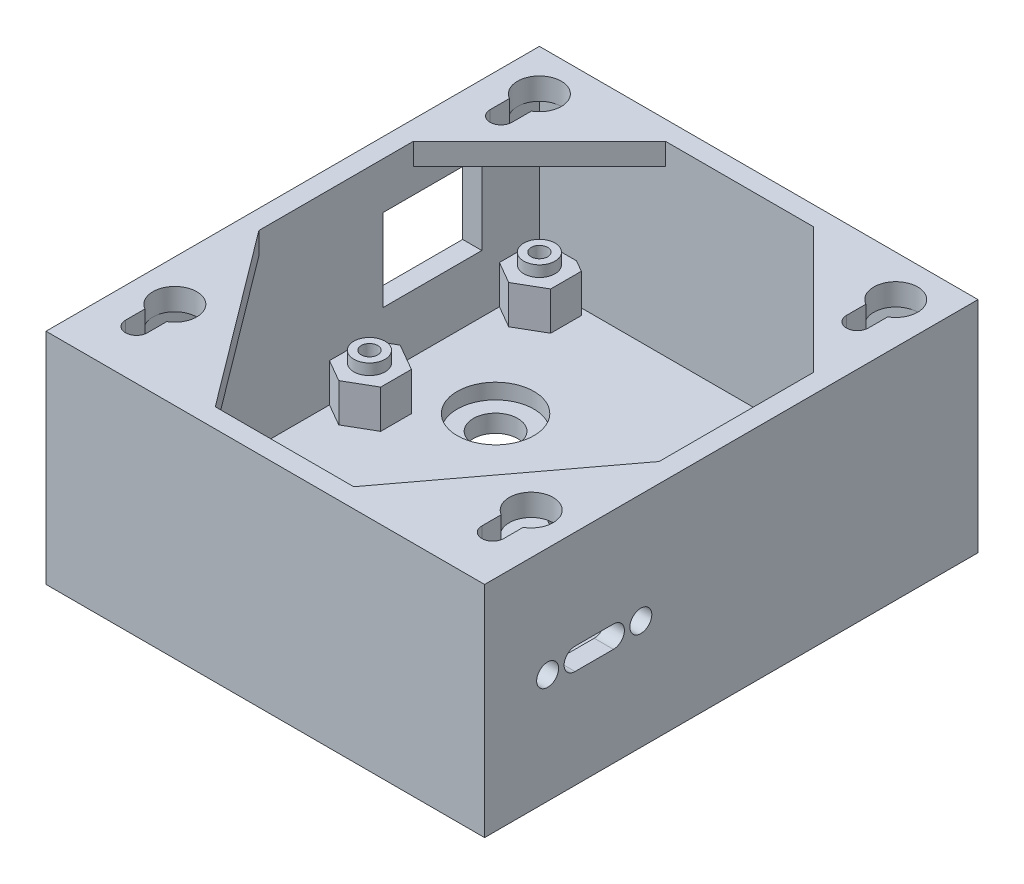
SolidWorks part; units mm, degrees
ref_plane "Front Plane" through (0, 0, 0) normal (0, 0, 1) x (1, 0, 0)
ref_plane "Top Plane" through (0, 0, 0) normal (0, 1, 0) x (1, 0, 0)
ref_plane "Right Plane" through (0, 0, 0) normal (1, 0, 0) x (0, 0, -1)
sketch "Sketch1" plane through (0, 0, 0) normal (0, 1, 0) x (1, 0, 0)
  line L1 (-40, -45) -> (40, -45)
  line L2 (-40, -45) -> (-40, 45)
  line L3 (-40, 45) -> (40, 45)
  line L4 (40, -45) -> (40, 45)
  line L5 (-40, -45) -> (40, 45) construction
  line L6 (-40, 45) -> (40, -45) construction
  point P0 (0, 0)
  dimension "D1" = 80
  dimension "D2" = 90
extrude "Boss-Extrude1" add sketch "Sketch1" along normal blind 6
sketch "Sketch4" plane through (0, 6, 0) normal (0, 1, 0) x (1, 0, 0)
  line L0 (40, -45) -> (40, 45) construction
  line L1 (-40, 45) -> (40, 45)
  line L2 (-40, 45) -> (-40, -45)
  line L3 (-40, -45) -> (40, -45)
  line L4 (40, 45) -> (40, -45)
  line L5 (-36.5, 41.5) -> (36.5, 41.5)
  line L6 (-36.5, 41.5) -> (-36.5, -41.5)
  line L7 (-36.5, -41.5) -> (36.5, -41.5)
  line L8 (36.5, 41.5) -> (36.5, -41.5)
  dimension "D1" = 3.5
  dimension "D2" = 3.5
  dimension "D3" = 3.5
  dimension "D4" = 3.5
extrude "Boss-Extrude2" add sketch "Sketch4" along normal blind 34 contours L2 L1 L4 L3 | L6 L5 L8 L7
sketch "Sketch5" plane through (0, 6, 0) normal (0, 1, 0) x (1, 0, 0)
  line L0 (-40, 45) -> (40, 45) construction
  line L1 (-36.5, 41.5) -> (-36.5, -41.5) construction
  line L2 (-36.5, 41.5) -> (-36.5, -41.5) construction
  circle A0 centre (-32.5, 37.5) radius 1.5
  circle A1 centre (-32.5, 6.5) radius 1.5
  dimension "D1" = 3
  dimension "D4" = 3
  dimension "D2" = 7.5
  dimension "D3" = 4
  dimension "D5" = 31
  dimension "D6" = 4
sketch "Sketch6" plane through (0, 6, 0) normal (0, 1, 0) x (1, 0, 0)
  line L0 (-40, 45) -> (-40, -45) construction
  line L1 (-40, 45) -> (40, 45) construction
  line L2 (-40, -45) -> (40, -45) construction
  circle A0 centre (-20, 17) radius 4.05
  circle A1 centre (-20, -25) radius 4.05
  dimension "D2" = 8.1
  dimension "D3" = 8.1
  dimension "D4" = 28
  dimension "D5" = 20
  dimension "D1" = 20
extrude "Cut-Extrude1" cut sketch "Sketch6" against normal blind 40
sketch "Sketch7" plane through (0, 6, 0) normal (0, 1, 0) x (1, 0, 0)
  circle A0 centre (-20, 17) radius 7
  circle A1 centre (-20, -25) radius 7
  dimension "D1" = 14
  dimension "D2" = 14
extrude "Cut-Extrude2" cut sketch "Sketch7" against normal blind 2.8
sketch "Sketch8" plane through (0, 6, 0) normal (0, 1, 0) x (1, 0, 0)
  line L0 (-36.5, 41.5) -> (-36.5, -41.5) construction
  line L1 (-29.65, 39.1454) -> (-32.5, 40.7909)
  line L2 (-32.5, 40.7909) -> (-35.35, 39.1454)
  line L3 (-35.35, 39.1454) -> (-35.35, 35.8546)
  line L4 (-35.35, 35.8546) -> (-32.5, 34.2091)
  line L5 (-32.5, 34.2091) -> (-29.65, 35.8546)
  line L6 (-29.65, 35.8546) -> (-29.65, 39.1454)
  line L8 (-29.65, 8.1454) -> (-32.5, 9.7909)
  line L9 (-32.5, 9.7909) -> (-35.35, 8.1454)
  line L10 (-35.35, 8.1454) -> (-35.35, 4.8546)
  line L11 (-35.35, 4.8546) -> (-32.5, 3.2091)
  line L12 (-32.5, 3.2091) -> (-29.65, 4.8546)
  line L13 (-29.65, 4.8546) -> (-29.65, 8.1454)
  circle A0 centre (-32.5, 37.5) radius 2.85 construction
  circle A1 centre (-32.5, 6.5) radius 2.85 construction
  point P40 (-33.925, 8.9682)
  dimension "D1" = 5.7
  dimension "D4" = 5.7
sketch "Sketch10" plane through (0, 6, 0) normal (0, 1, 0) x (1, 0, 0)
  line L1 (-32.5, 43.1003) -> (-37.35, 40.3001)
  line L2 (-37.35, 40.3001) -> (-37.35, 34.6999)
  line L3 (-37.35, 34.6999) -> (-32.5, 31.8997)
  line L4 (-32.5, 31.8997) -> (-27.65, 34.6999)
  line L5 (-27.65, 34.6999) -> (-27.65, 40.3001)
  line L6 (-27.65, 40.3001) -> (-32.5, 43.1003)
  line L19 (-27.65, 9.3001) -> (-32.5, 12.1003)
  line L20 (-32.5, 12.1003) -> (-37.35, 9.3001)
  line L21 (-37.35, 9.3001) -> (-37.35, 3.6999)
  line L22 (-37.35, 3.6999) -> (-32.5, 0.8997)
  line L23 (-32.5, 0.8997) -> (-27.65, 3.6999)
  line L24 (-27.65, 3.6999) -> (-27.65, 9.3001)
  line L25 (-36.5, 41.5) -> (-36.5, -41.5) construction
  line L27 (-32.5, 34.2091) -> (-29.65, 35.8546) construction
  line L28 (-32.5, 3.2091) -> (-29.65, 4.8546) construction
  circle A0 centre (-32.5, 37.5) radius 4.85 construction
  circle A3 centre (-32.5, 6.5) radius 4.85 construction
  dimension "D1" = 2
  dimension "D2" = 2
extrude "Boss-Extrude3" add sketch "Sketch10" along normal blind 7
sketch "Sketch11" plane through (0, 13, 0) normal (0, 1, 0) x (1, 0, 0)
  circle A0 centre (-32.5, 37.5) radius 2.85
  circle A3 centre (-32.5, 6.5) radius 2.85
  dimension "D1" = 5.7
  dimension "D2" = 5.7
extrude "Boss-Extrude4" add sketch "Sketch11" along normal blind 2
extrude "Cut-Extrude3" cut sketch "Sketch5" against normal blind 6 and the other way blind 9
extrude "Cut-Extrude4" cut sketch "Sketch8" against normal through all and the other way blind 6
sketch "Sketch12" plane through (-36.5, 0, 0) normal (1, 0, 0) x (0, 0, -1)
  line L0 (45, 0) -> (-45, 0) construction
  line L1 (31, 16.5) -> (13, 16.5)
  line L2 (31, 16.5) -> (31, 31.5)
  line L3 (31, 31.5) -> (13, 31.5)
  line L4 (13, 16.5) -> (13, 31.5)
  line L5 (45, 40) -> (45, 0) construction
  dimension "D1" = 18
  dimension "D2" = 15
  dimension "16.5mm" = 16.5
  dimension "D4" = 14
extrude "Cut-Extrude6" cut sketch "Sketch12" against normal blind 3.5
sketch "Sketch15" plane through (-36.5, 0, 0) normal (1, 0, 0) x (0, 0, -1)
  line L0 (45, 40) -> (45, 0) construction
  line L1 (-29.75, 32.9904) -> (-41, 26.4952)
  line L2 (-41, 26.4952) -> (-41, 13.5048)
  line L3 (-41, 13.5048) -> (-29.75, 7.0096)
  line L4 (-29.75, 7.0096) -> (-18.5, 13.5048)
  line L5 (-18.5, 13.5048) -> (-18.5, 26.4952)
  line L6 (-18.5, 26.4952) -> (-29.75, 32.9904)
  line L8 (13, 31.5) -> (13, 16.5) construction
  line L9 (-45, 40) -> (-45, 0) construction
  circle A1 centre (-29.75, 20) radius 11.25 construction
  point P11 (45, 20)
  dimension "D1" = 22.5
  dimension "D2" = 4
sketch "Sketch17" plane through (-40, 0, 0) normal (-1, 0, 0) x (0, 0, 1)
  circle A0 centre (29.75, 20) radius 8
  dimension "D1" = 16
extrude "Cut-Extrude8" cut sketch "Sketch17" against normal blind 2
extrude "Cut-Extrude9" cut sketch "Sketch15" against normal blind 1.5
sketch "Sketch23" plane through (0, 40, 0) normal (0, 1, 0) x (1, 0, 0)
  line L0 (-10, -45) -> (-40, -5)
  line L1 (-40, -45) -> (40, -45) construction
  line L2 (-40, 45) -> (-40, -45) construction
  line L3 (-40, -5) -> (-40, -45)
  line L4 (-40, -45) -> (-10, -45)
  line L5 (40, -45) -> (10, -45)
  line L6 (40, 45) -> (40, -45) construction
  line L7 (10, -45) -> (40, -5)
  line L8 (40, -5) -> (40, -45)
  line L9 (-40, 45) -> (-40, 15)
  line L10 (-40, 15) -> (-10, 45)
  line L11 (-40, 45) -> (40, 45) construction
  line L12 (-10, 45) -> (-40, 45)
  line L13 (10, 45) -> (40, 45)
  line L14 (40, 45) -> (40, 15)
  line L15 (40, 15) -> (10, 45)
  dimension "D1" = 30
  dimension "40" = 40
  dimension "D3" = 30
  dimension "D4" = 40
  dimension "D5" = 30
  dimension "D6" = 30
  dimension "D7" = 30
  dimension "D8" = 30
sketch "Sketch29" plane through (0, 6, 0) normal (0, 1, 0) x (1, 0, 0)
  line L0 (4, 18.9) -> (4, 8.1) construction
  line L1 (8, 18.9) -> (8, 8.1)
  line L2 (0, 18.9) -> (0, 8.1)
  line L3 (-36.5, 41.5) -> (-36.5, -41.5) construction
  line L4 (-29.7282, 41.5) -> (36.5, 41.5) construction
  arc A0 (8, 18.9) -> (0, 18.9) centre (4, 18.9) ccw
  arc A1 (0, 8.1) -> (8, 8.1) centre (4, 8.1) ccw
  point P2 (4, 13.5)
  dimension "D1" = 10.8
  dimension "D2" = 8
  dimension "D3" = 36.5
  dimension "D4" = 22.6
extrude "Cut-Extrude14" cut sketch "Sketch29" against normal blind 10
sketch "Sketch30" plane through (40, 0, 0) normal (1, 0, 0) x (0, 0, -1)
  line L0 (-28.5, 20) -> (-21.5, 20) construction
  line L1 (-28.5, 22) -> (-21.5, 22)
  line L2 (-28.5, 18) -> (-21.5, 18)
  line L3 (45, 40) -> (-45, 40) construction
  line L4 (-45, 40) -> (-45, 0) construction
  line L5 (-45, 0) -> (45, 0) construction
  arc A0 (-28.5, 22) -> (-28.5, 18) centre (-28.5, 20) ccw
  arc A1 (-21.5, 18) -> (-21.5, 22) centre (-21.5, 20) ccw
  circle A2 centre (-33.5, 20) radius 2
  circle A3 centre (-16.5, 20) radius 2
  point P2 (-25, 20)
  point P11 (0, 0)
  point P16 (-16.5, 19.9997)
  point P17 (-25, 20)
  point P22 (0, 0)
  point P23 (0, 0)
  dimension "D1" = 7
  dimension "D3" = 4
  dimension "D4" = 4
  dimension "D2" = 4
  dimension "D6" = 5
  dimension "D7" = 5
  dimension "D8" = 20
  dimension "D9" = 20
extrude "Cut-Extrude15" cut sketch "Sketch30" against normal blind 10
extrude "Boss-Extrude6" add sketch "Sketch23" against normal blind 4
sketch "Sketch26" plane through (0, 40, 0) normal (0, 1, 0) x (1, 0, 0)
  line L0 (-40, 45) -> (40, 45) construction
  line L1 (-40, 45) -> (-40, -45) construction
  line L2 (40, 45) -> (40, -45) construction
  line L3 (-40, -45) -> (40, -45) construction
  circle A0 centre (-32.5, 37.5) radius 4
  circle A1 centre (32.5, 37.5) radius 4
  circle A2 centre (32.5, -29) radius 4
  circle A3 centre (-32.5, -29) radius 4
  dimension "D1" = 7.5
  dimension "D2" = 8
  dimension "D6" = 8
  dimension "D7" = 8
  dimension "D10" = 8
  dimension "D3" = 7.5
  dimension "D4" = 7.5
  dimension "D5" = 7.5
  dimension "D8" = 16
  dimension "D9" = 7.5
sketch "Sketch27" plane through (0, 40, 0) normal (0, 1, 0) x (1, 0, 0)
  line L0 (-32.5, 37.5) -> (-32.5, 30.5) construction
  line L1 (-30.5, 37.5) -> (-30.5, 30.5)
  line L2 (-34.5, 37.5) -> (-34.5, 30.5)
  line L3 (32.5, 37.5) -> (32.5, 30.5) construction
  line L4 (34.5, 37.5) -> (34.5, 30.5)
  line L5 (30.5, 37.5) -> (30.5, 30.5)
  line L6 (32.5, -29) -> (32.5, -36) construction
  line L7 (34.5, -29) -> (34.5, -36)
  line L8 (30.5, -29) -> (30.5, -36)
  line L9 (-32.5, -29) -> (-32.5, -36) construction
  line L10 (-30.5, -29) -> (-30.5, -36)
  line L11 (-34.5, -29) -> (-34.5, -36)
  arc A0 (-30.5, 37.5) -> (-34.5, 37.5) centre (-32.5, 37.5) ccw
  arc A1 (-34.5, 30.5) -> (-30.5, 30.5) centre (-32.5, 30.5) ccw
  arc A2 (34.5, 37.5) -> (30.5, 37.5) centre (32.5, 37.5) ccw
  arc A3 (30.5, 30.5) -> (34.5, 30.5) centre (32.5, 30.5) ccw
  arc A4 (34.5, -29) -> (30.5, -29) centre (32.5, -29) ccw
  arc A5 (30.5, -36) -> (34.5, -36) centre (32.5, -36) ccw
  arc A6 (-30.5, -29) -> (-34.5, -29) centre (-32.5, -29) ccw
  arc A7 (-34.5, -36) -> (-30.5, -36) centre (-32.5, -36) ccw
  point P3 (-32.5, 34)
  point P11 (32.5, 34)
  point P18 (32.5, -32.5)
  point P24 (-32.5, -32.5)
  dimension "D1" = 7
  dimension "D2" = 4
  dimension "D3" = 4
  dimension "D4" = 7
  dimension "D5" = 4
  dimension "D6" = 4
  dimension "D7" = 7
  dimension "D8" = 7
extrude "Cut-Extrude12" cut sketch "Sketch27" against normal blind 4
extrude "Cut-Extrude13" cut sketch "Sketch26" against normal blind 4
